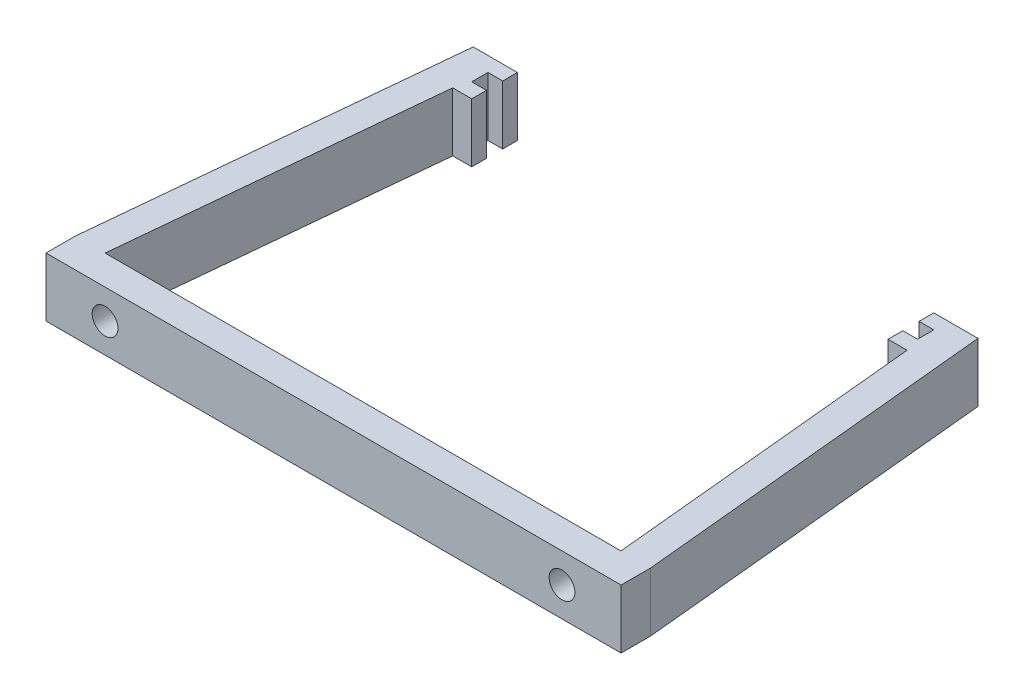
SolidWorks part; units mm, degrees
ref_plane "Plano frontal" through (0, 0, 0) normal (0, 0, 1) x (1, 0, 0)
ref_plane "Plano superior" through (0, 0, 0) normal (0, 1, 0) x (1, 0, 0)
ref_plane "Plano direito" through (0, 0, 0) normal (1, 0, 0) x (0, 0, -1)
sketch "Esboço1" plane through (0, 0, 0) normal (0, 0, 1) x (1, 0, 0)
  line L0 (-31, 0) -> (31, 0) construction
  line L2 (-35, 4) -> (35, 4)
  line L3 (-35, 4) -> (-35, -4)
  line L4 (-35, -4) -> (35, -4)
  line L5 (35, 4) -> (35, -4)
  line L6 (-35, 4) -> (35, -4) construction
  line L7 (-35, -4) -> (35, 4) construction
  circle A0 centre (-31, 0) radius 1.75
  circle A1 centre (31, 0) radius 1.75
  point P4 (0, 0)
  point P5 (0, 0)
  dimension "D1" = 3.5
  dimension "D2" = 62
  dimension "D3" = 70
  dimension "D4" = 8
extrude "Ressalto-extrusão1" add sketch "Esboço1" along normal blind 4
sketch "Esboço2" plane through (0, 4, 0) normal (0, 1, 0) x (1, 0, 0)
  line L0 (-35, 0) -> (-35, -4)
  line L1 (35, 0) -> (-35, 0) construction
  line L2 (-39.0187, 0) -> (-34.25, 49.2)
  line L3 (-34.25, 49.2) -> (-28.25, 49.2)
  line L4 (-28.25, 49.2) -> (-28.25, 47.2)
  line L5 (-28.25, 47.2) -> (-30.25, 47.2)
  line L6 (-30.25, 47.2) -> (-30.25, 45)
  line L7 (-30.25, 45) -> (-28.25, 45)
  line L8 (-28.25, 45) -> (-28.25, 43)
  line L9 (-28.25, 43) -> (-30.8322, 43)
  line L10 (-30.8322, 43) -> (-35, 0)
  line L11 (0, 29.2585) -> (0, 0) construction
  line L12 (-35, -4) -> (-35, 0) construction
  line L13 (-39.0187, 0) -> (-39.0187, -4)
  line L14 (-39.0187, -4) -> (-35, -4)
  line L15 (39.0187, -4) -> (35, -4)
  line L16 (39.0187, 0) -> (39.0187, -4)
  line L17 (30.8322, 43) -> (35, 0)
  line L18 (28.25, 43) -> (30.8322, 43)
  line L19 (28.25, 45) -> (28.25, 43)
  line L20 (30.25, 45) -> (28.25, 45)
  line L21 (30.25, 47.2) -> (30.25, 45)
  line L22 (28.25, 47.2) -> (30.25, 47.2)
  line L23 (28.25, 49.2) -> (28.25, 47.2)
  line L24 (34.25, 49.2) -> (28.25, 49.2)
  line L25 (39.0187, 0) -> (34.25, 49.2)
  line L26 (35, 0) -> (35, -4)
  point P2 (-38.6794, 0)
  point P6 (0, 0)
  dimension "D1" = 2.2
  dimension "D2" = 2
  dimension "D3" = 6
  dimension "D4" = 2
  dimension "D5" = 4
  dimension "D6" = 60.5
  dimension "D7" = 43
extrude "Ressalto-extrusão2" add sketch "Esboço2" against normal up to surface (8 mm away) up to face at (0, -4, 2)
